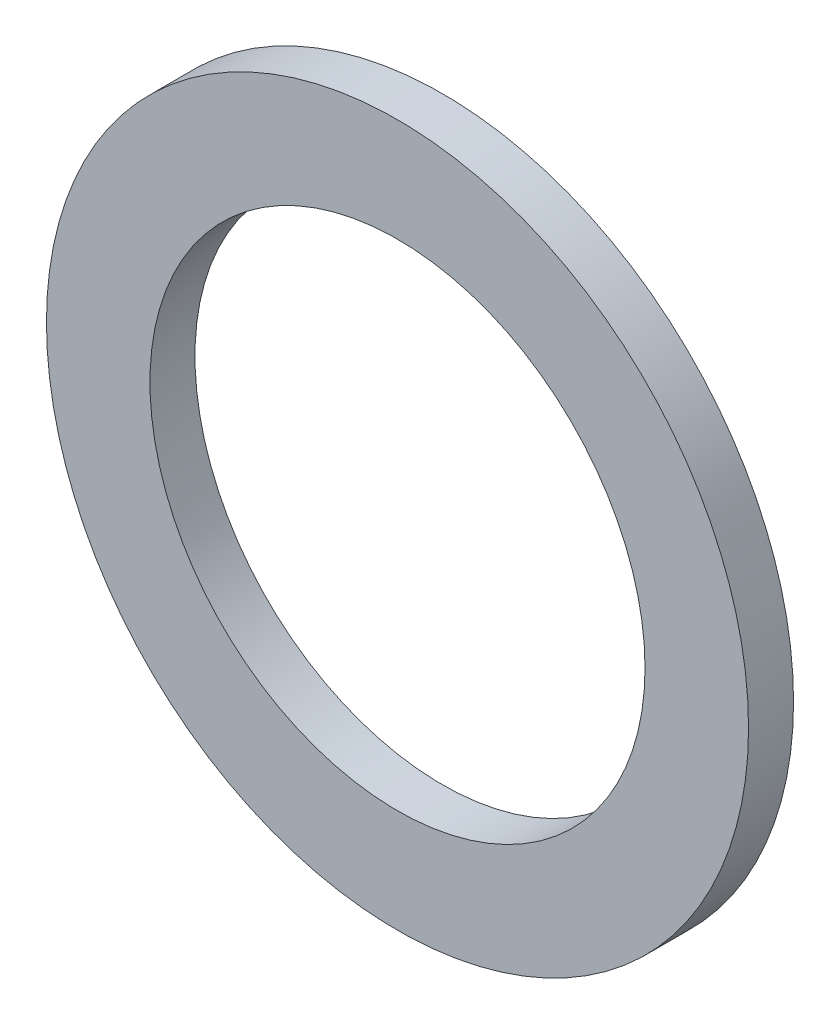
SolidWorks part; units mm, degrees
ref_plane "前视基准面" through (0, 0, 0) normal (0, 0, 1) x (1, 0, 0)
ref_plane "上视基准面" through (0, 0, 0) normal (0, 1, 0) x (1, 0, 0)
ref_plane "右视基准面" through (0, 0, 0) normal (1, 0, 0) x (0, 0, -1)
sketch "草图1" plane through (0, 0, 0) normal (0, 0, 1) x (1, 0, 0)
  circle A0 centre (0, 0) radius 39
  circle A1 centre (0, 0) radius 27.5
  dimension "D1" = 55
  dimension "D2" = 78
extrude "凸台-拉伸1" add sketch "草图1" along normal blind 5
